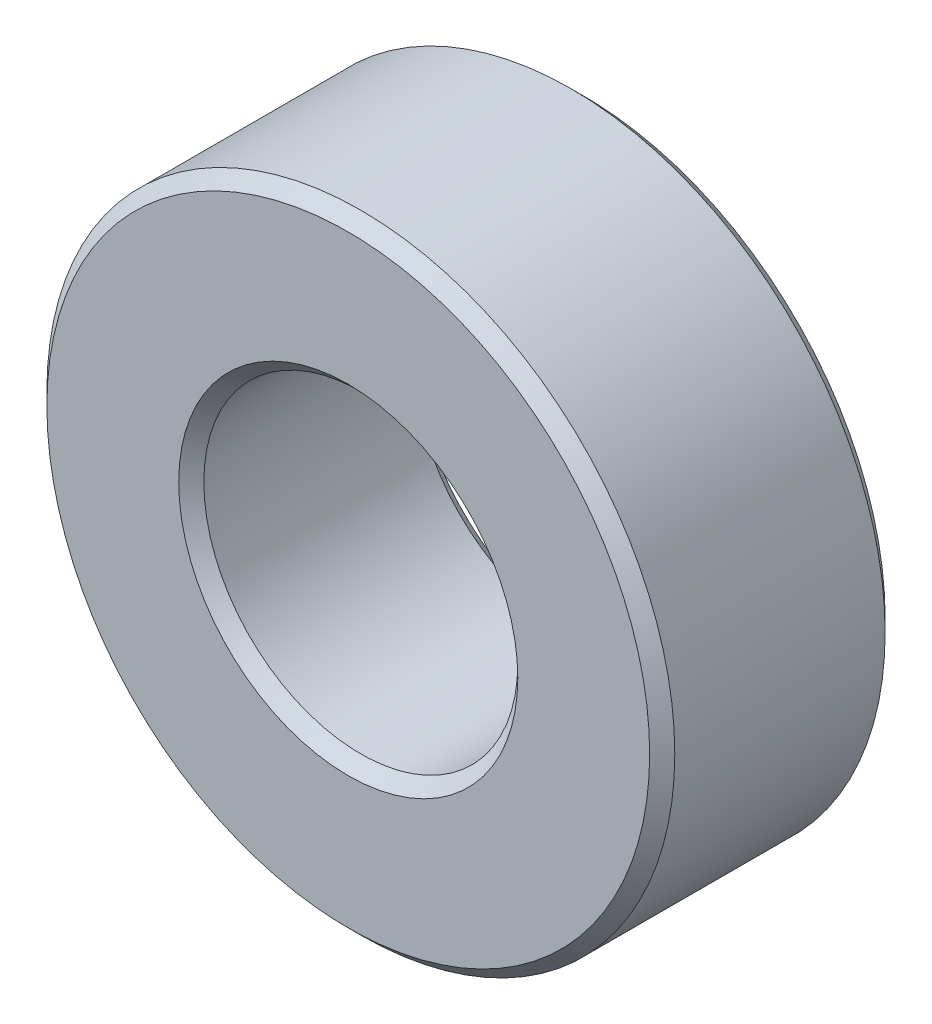
SolidWorks part; units mm, degrees
ref_plane "Front Plane" through (0, 0, 0) normal (0, 0, 1) x (1, 0, 0)
ref_plane "Top Plane" through (0, 0, 0) normal (0, 1, 0) x (1, 0, 0)
ref_plane "Right Plane" through (0, 0, 0) normal (1, 0, 0) x (0, 0, -1)
sketch "Sketch1" plane through (0, 0, 0) normal (0, 0, 1) x (1, 0, 0)
  circle A0 centre (0, 0) radius 6.35
  circle A1 centre (0, 0) radius 3.175
  dimension "D1" = 12.7
  dimension "D2" = 6.35
extrude "Boss-Extrude1" add sketch "Sketch1" along normal blind 4.7625
chamfer "Chamfer1" distance 0.254 angle 45 4 edges at (3.175, 0, 0) (3.175, 0, 4.7625) (6.35, 0, 0) (6.35, 0, 4.7625)
